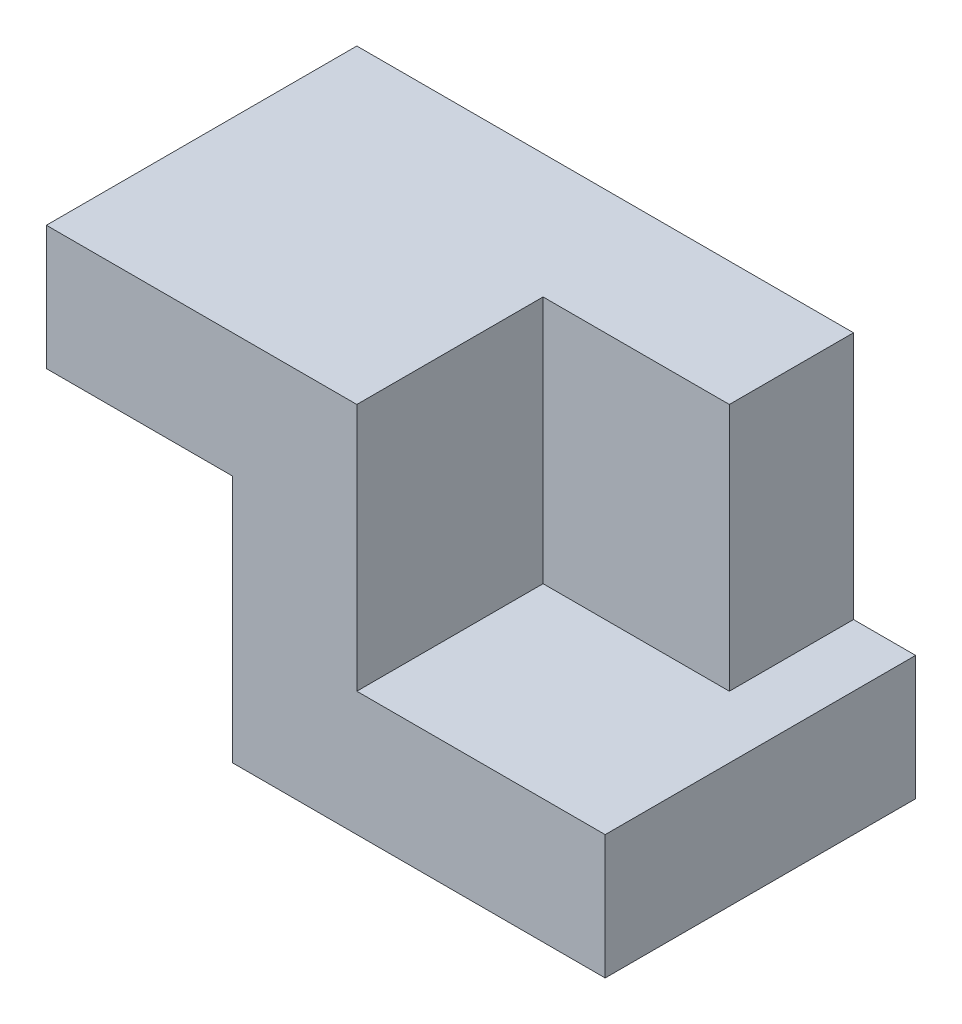
SolidWorks part; units mm, degrees
ref_plane "Alzado" through (0, 0, 0) normal (0, 0, 1) x (1, 0, 0)
ref_plane "Planta" through (0, 0, 0) normal (0, 1, 0) x (1, 0, 0)
ref_plane "Vista lateral" through (0, 0, 0) normal (1, 0, 0) x (0, 0, -1)
sketch "Croquis2" plane through (0, 0, 0) normal (0, 0, 1) x (1, 0, 0)
  line L1 (-45, -30) -> (45, -30)
  line L2 (-45, -30) -> (-45, 30)
  line L3 (-45, 30) -> (45, 30)
  line L4 (45, -30) -> (45, 30)
  line L5 (-45, -30) -> (45, 30) construction
  line L6 (-45, 30) -> (45, -30) construction
  point P0 (0, 0)
  dimension "D1" = 60
  dimension "D2" = 90
extrude "Saliente-Extruir1" add sketch "Croquis2" along normal blind 50
sketch "Croquis3" plane through (-45, 0, 0) normal (-1, 0, 0) x (0, 0, 1)
  line L0 (50, 30) -> (50, -30) construction
  line L1 (0, -30) -> (50, -30)
  line L2 (0, -30) -> (0, 10)
  line L3 (0, 10) -> (50, 10)
  line L4 (50, -30) -> (50, 10)
  dimension "D1" = 40
extrude "Cortar-Extruir3" cut sketch "Croquis3" against normal blind 30
sketch "Croquis5" plane through (0, 30, 0) normal (0, 1, 0) x (1, 0, 0)
  line L0 (45, -50) -> (-45, -50) construction
  line L1 (45, 0) -> (35, 0)
  line L2 (45, 0) -> (45, -50)
  line L3 (45, -50) -> (35, -50)
  line L4 (35, 0) -> (35, -50)
  line L6 (35, -50) -> (5, -50)
  line L7 (35, -50) -> (35, -20)
  line L8 (35, -20) -> (5, -20)
  line L9 (5, -50) -> (5, -20)
  line M5 (45, 0) -> (-45, 0)
  line M7 (-45, -50) -> (45, -50)
  line M8 (45, -50) -> (45, 0)
  dimension "D1" = 10
  dimension "D2" = 30
  dimension "D3" = 30
extrude "Cortar-Extruir4" cut sketch "Croquis5" against normal blind 40 contours L9 L4 L8 M7 | L4 M5 M7 M8
